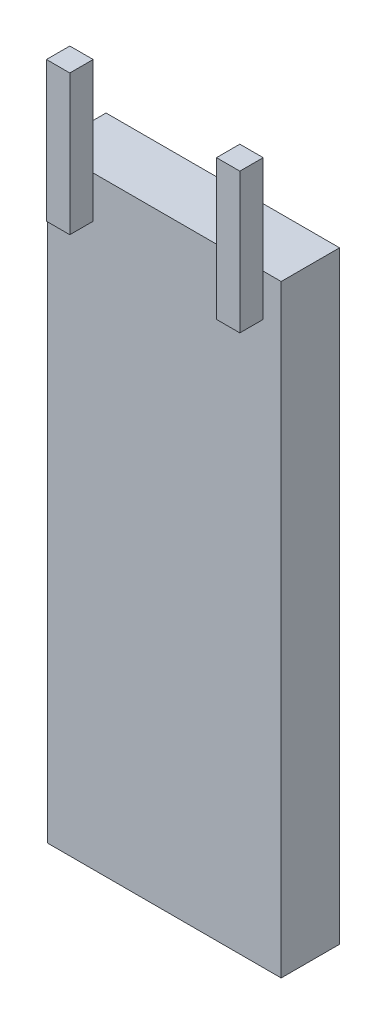
SolidWorks part; units mm, degrees
ref_plane "Přední rovina" through (0, 0, 0) normal (0, 0, 1) x (1, 0, 0)
ref_plane "Horní rovina" through (0, 0, 0) normal (0, 1, 0) x (1, 0, 0)
ref_plane "Pravá rovina" through (0, 0, 0) normal (1, 0, 0) x (0, 0, -1)
sketch "Skica1" plane through (0, 0, 0) normal (0, 0, 1) x (1, 0, 0)
  line L1 (-0.8, -0.425) -> (0.8, -0.425)
  line L2 (-0.8, -0.425) -> (-0.8, 0.425)
  line L3 (-0.8, 0.425) -> (0.8, 0.425)
  line L4 (0.8, -0.425) -> (0.8, 0.425)
  line L5 (-0.8, -0.425) -> (0.8, 0.425) construction
  line L6 (-0.8, 0.425) -> (0.8, -0.425) construction
  point P0 (0, 0)
  dimension "D1" = 1.6
  dimension "D2" = 0.85
extrude "Přidat vysunutím1" add sketch "Skica1" along normal blind 0.45
sketch "Skica2" plane through (0, 0, 0) normal (0, 0, -1) x (-1, 0, 0)
  line L0 (0.8, -0.425) -> (-0.8, -0.425) construction
  line L1 (-3.0623, -2.925) -> (2.9377, -2.925)
  line L2 (-3.0623, -2.925) -> (-3.0623, 12.575)
  line L3 (-3.0623, 12.575) -> (2.9377, 12.575)
  line L4 (2.9377, -2.925) -> (2.9377, 12.575)
  dimension "D1" = 15.5
  dimension "D2" = 6
  dimension "D3" = 2.5
extrude "Přidat vysunutím2" add sketch "Skica2" along normal blind 1.5
sketch "Skica4" plane through (0, 0, 0) normal (0, 1, 0) x (1, 0, 0)
  line L0 (-2.9377, 0) -> (3.0623, 0) construction
  line L1 (-2.369, 0) -> (-1.769, 0)
  line L2 (-2.369, 0) -> (-2.369, -0.6)
  line L3 (-2.369, -0.6) -> (-1.769, -0.6)
  line L4 (-1.769, 0) -> (-1.769, -0.6)
  line L6 (1.9999, 0) -> (2.5999, 0)
  line L7 (1.9999, 0) -> (1.9999, -0.6)
  line L8 (1.9999, -0.6) -> (2.5999, -0.6)
  line L9 (2.5999, 0) -> (2.5999, -0.6)
  dimension "D1" = 0.6
extrude "Přidat vysunutím4" add sketch "Skica4" along normal blind 3.6 from offset 11.5
sketch "Skica5" plane through (0, 0, 0.45) normal (0, 0, 1) x (1, 0, 0)
sketch "Skica6" plane through (0, 0, 0.45) normal (0, 0, 1) x (1, 0, 0)
  line L1 (-0.8, -0.425) -> (0.8, -0.425)
  line L2 (-0.8, -0.425) -> (-0.8, 0.425)
  line L3 (-0.8, 0.425) -> (0.8, 0.425)
  line L4 (0.8, -0.425) -> (0.8, 0.425)
  line L5 (-0.8, -0.425) -> (0.8, 0.425) construction
  line L6 (-0.8, 0.425) -> (0.8, -0.425) construction
  point P0 (0, 0)
extrude "Odebrat vysunutím1" cut sketch "Skica6" against normal up to vertex (0.45 mm away)
sketch "Skica7" plane through (0, 0, 0) normal (0, 0, 1) x (1, 0, 0)
  circle A0 centre (0, 0) radius 2.596
curve "Šroubovice/spirála1"
